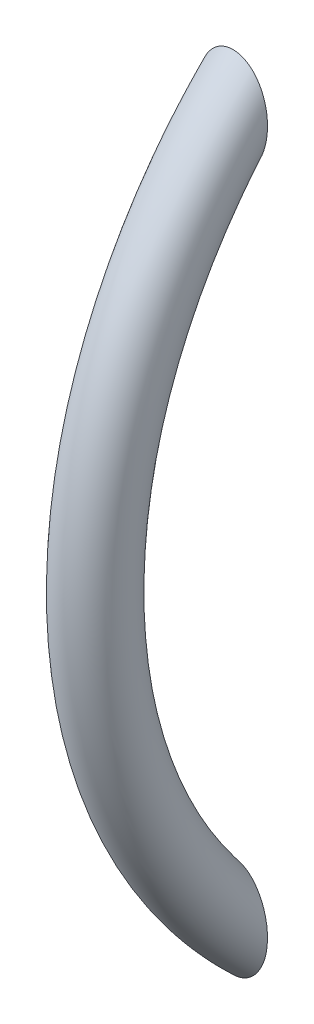
SolidWorks part; units mm, degrees
material "Acciaio inossidabile al cromo"
ref_plane "Front Plane" through (0, 0, 0) normal (0, 0, 1) x (1, 0, 0)
ref_plane "Top Plane" through (0, 0, 0) normal (0, 1, 0) x (1, 0, 0)
ref_plane "Right Plane" through (0, 0, 0) normal (1, 0, 0) x (0, 0, -1)
ref_plane "Plane1" through (0, -48, 0) normal (0, 1, 0) x (-1, 0, 0)
sketch "Sketch1" plane through (0, -48, 0) normal (0, -1, 0) x (1, 0, 0)
  line L0 (-43.2558, -55) -> (41.0789, -55) construction
  line L3 (50, 0) -> (-50, 0) construction
  line L4 (0, -50) -> (0, 50) construction
  circle A0 centre (0, 20) radius 5
  dimension "D1" = 10
  dimension "D2" = 75
  dimension "D3" = 20
revolve "Revolve1" add sketch "Sketch1" angle 360 about L0
sketch "Sketch2" plane through (0, 0, 0) normal (1, 0, 0) x (0, 0, -1)
  line L0 (0, 50) -> (0, -50) construction
  line L1 (0, -135) -> (140, -135)
  line L2 (0, -135) -> (0, 35)
  line L3 (0, 35) -> (140, 35)
  line L4 (140, -135) -> (140, 35)
  line L5 (50, 0) -> (-50, 0) construction
  dimension "D1" = 140
  dimension "D2" = 35
  dimension "D3" = 170
extrude "Cut-Extrude1" cut sketch "Sketch2" against normal through all and the other way through all
sketch "Sketch4" plane through (0, 0, 0) normal (0, 0, 1) x (1, 0, 0)
  circle A0 centre (0, 0) radius 2.5
  circle A1 centre (0, -96) radius 2.5
  dimension "D1" = 5
  dimension "D3" = 5
  dimension "D2" = 96
extrude "Cut-Extrude2" cut sketch "Sketch4" along normal blind 5
move or copy body "Corpo-Sposta/copia1" [suppressed] bodies to move or copy 109
